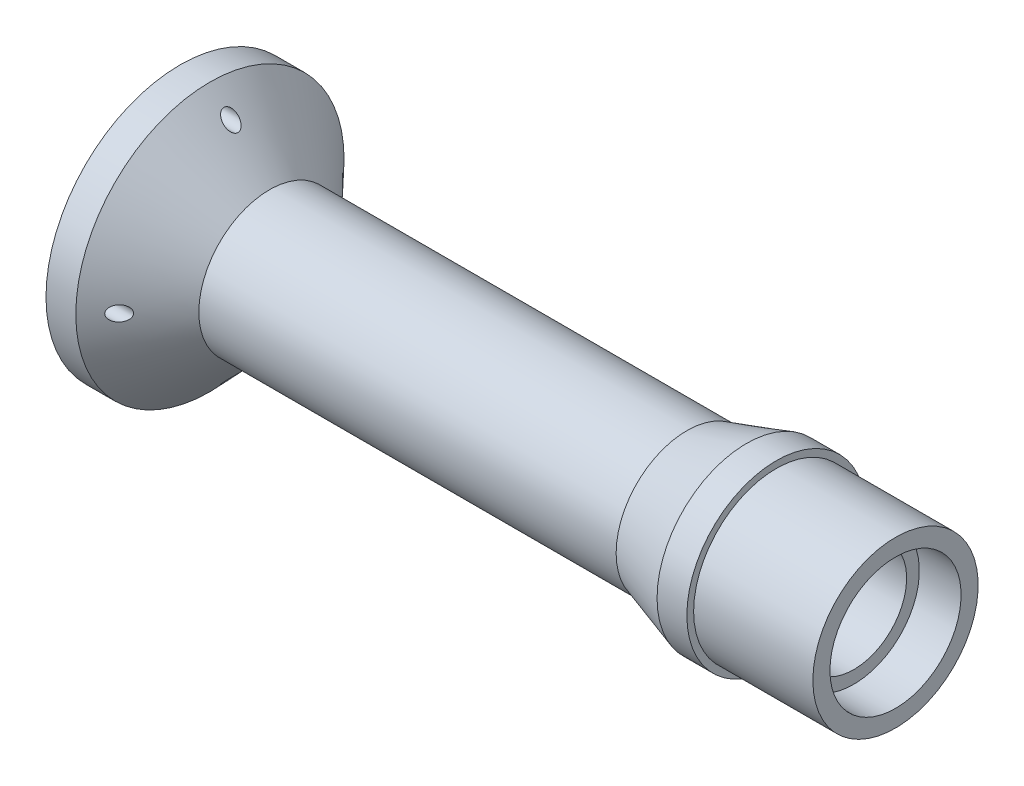
SolidWorks part; units mm, degrees
ref_plane "Ön Düzlem" through (0, 0, 0) normal (0, 0, 1) x (1, 0, 0)
ref_plane "Üst Düzlem" through (0, 0, 0) normal (0, 1, 0) x (1, 0, 0)
ref_plane "Sağ Düzlem" through (0, 0, 0) normal (1, 0, 0) x (0, 0, -1)
sketch "Çizim1" plane through (0, 0, 0) normal (0, 0, 1) x (1, 0, 0)
  line L0 (0, 0) -> (100.7377, 0) construction
  line L1 (-14.0843, 8.864) -> (105.9157, 8.864)
  line L2 (-14.0843, 8.864) -> (-14.0843, 22.5)
  line L3 (-14.0843, 22.5) -> (-9.0843, 22.5)
  line L4 (-9.0843, 22.5) -> (0.9157, 11.864)
  line L5 (0.9157, 11.864) -> (70.9157, 11.864)
  line L6 (70.9157, 11.864) -> (80.9157, 15)
  line L7 (80.9157, 15) -> (85.9157, 15)
  line L8 (85.9157, 15) -> (85.9157, 13.864)
  line L9 (85.9157, 13.864) -> (105.9157, 13.864)
  line L10 (105.9157, 13.864) -> (105.9157, 8.864)
  line L11 (98.9157, 8.864) -> (98.9157, 11)
  line L12 (98.9157, 11) -> (105.9157, 11)
  point P15 (80.9157, 15)
  dimension "D1" = 120
  dimension "D2" = 5
  dimension "D3" = 20
  dimension "D4" = 25
  dimension "D5" = 7
  dimension "D6" = 10
  dimension "D7" = 5
  dimension "D8" = 15
  dimension "D9" = 3
  dimension "D10" = 11
  dimension "D11" = 10
  dimension "D12" = 22.5
revolve "Döndür1" add sketch "Çizim1" angle 360 about L0
sketch "Çizim2" plane through (-14.0843, 0, 0) normal (-1, 0, 0) x (0, 0, 1)
  circle A0 centre (0, 18.75) radius 1.25
  dimension "D1" = 2.5
  dimension "D2" = 18.75
extrude "Kes-Ekstrüzyon1" cut sketch "Çizim2" against normal blind 16
pattern_circular "Dairesel Kaplama1" count 4 over 360 about axis through (0, 0, 0) along (1, 0, 0) of "Kes-Ekstrüzyon1"
